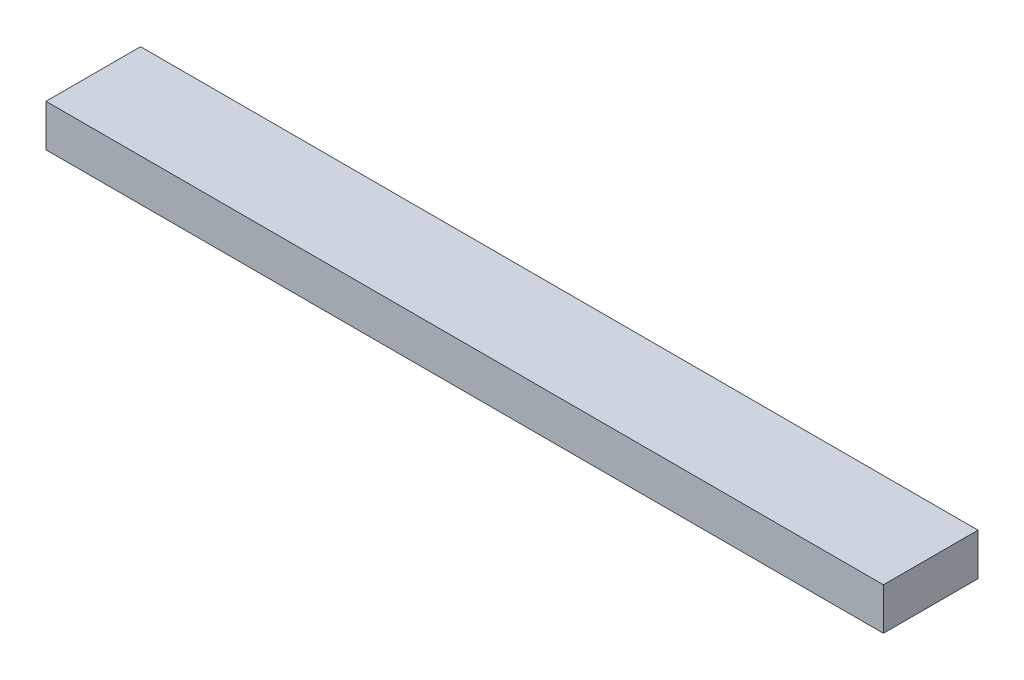
SolidWorks part; units mm, degrees
material "MDF"
ref_plane "Front Plane" through (0, 0, 0) normal (0, 0, 1) x (1, 0, 0)
ref_plane "Top Plane" through (0, 0, 0) normal (0, 1, 0) x (1, 0, 0)
ref_plane "Right Plane" through (0, 0, 0) normal (1, 0, 0) x (0, 0, -1)
sketch "Sketch1" plane through (0, 0, 0) normal (0, 0, 1) x (1, 0, 0)
  line L0 (0, -297.4265) -> (0, 297.4265) construction
  line L1 (-126.4888, -311.15) -> (126.4888, -311.15)
  line L2 (-126.4888, -311.15) -> (-126.4888, -298.45)
  line L3 (-126.4888, -298.45) -> (126.4888, -298.45)
  line L4 (0, -311.15) -> (0, -298.45) construction
  line L5 (126.4888, -311.15) -> (126.4888, -298.45)
  dimension "D1" = 12.7
extrude "Boss-Extrude1" add sketch "Sketch1" along normal up to surface (28.575 mm away)
hole_wizard "Hole1" positions "Sketch2" profile "Sketch3" legacy
sketch "Sketch2" plane through (0, 0, -25.4) normal (0, 0, -1) x (-1, 0, 0)
  line L0 (218.5638, 0) -> (218.5638, -437.642) construction
  line L4 (104.2638, 0) -> (104.2638, -298.45) construction
  line L13 (120.1388, -460.375) -> (120.1388, -311.15) construction
  line L16 (126.4888, -311.15) -> (113.7888, -311.15) construction
  line L18 (126.4888, -304.8) -> (-126.4888, -304.8) construction
  line L22 (94.7388, -276.225) -> (-94.7388, -276.225) construction
  line L24 (-94.7388, -285.75) -> (-94.7388, -266.7) construction
  line L26 (94.7388, -285.75) -> (94.7388, -266.7) construction
  line L27 (-94.7388, 0) -> (-94.7388, -19.05) construction
  line L29 (94.7388, 0) -> (94.7388, -19.05) construction
  line L31 (94.7388, -9.525) -> (-94.7388, -9.525) construction
  point P15 (218.5638, -31.75)
  point P17 (218.5638, -218.821)
  point P19 (218.5638, -418.592)
  point P28 (104.2638, -19.05)
  point P30 (104.2638, -149.225)
  point P32 (104.2638, -279.4)
  point P69 (120.1388, -330.2)
  point P71 (120.1388, -441.325)
  point P76 (-120.1388, -441.325)
  point P77 (-120.1388, -330.2)
  point P80 (-104.2638, -279.4)
  point P81 (-104.2638, -149.225)
  point P82 (-104.2638, -19.05)
  point P83 (-218.5638, -418.592)
  point P84 (-218.5638, -218.821)
  point P85 (-218.5638, -31.75)
  point P99 (0, -304.8)
  point P101 (107.4388, -304.8)
  point P103 (-107.4388, -304.8)
  point P127 (75.6888, -276.225)
  point P129 (0, -276.225)
  point P131 (-75.6888, -276.225)
  point P152 (75.6888, -9.525)
  point P154 (0, -9.525)
  point P156 (-75.6888, -9.525)
sketch "Sketch3" plane through (75.6888, -9.525, -25.4) normal (1, 0, 0) x (0, 1, 0)
  line L0 (0, 0) -> (0, 39.0539)
  line L1 (0, 39.0539) -> (1.5875, 38.1)
  line L2 (1.5875, 38.1) -> (1.5875, 4.0177)
  line L3 (1.5875, 4.0177) -> (5.08, 0)
  line L4 (5.08, 0) -> (0, 0)
  line L5 (0, -14.3089) -> (0, 102.4216) construction
  line L6 (0, 39.0539) -> (-1.5875, 38.1) construction
  line L7 (-1.5875, 4.0177) -> (-5.08, 0) construction
  dimension "Diameter" = 3.175
  dimension "Depth" = 38.1
  dimension "C-Sink Diameter" = 10.16
  dimension "C-Sink Angle" = 82
  dimension "Drill Angle" = 118
